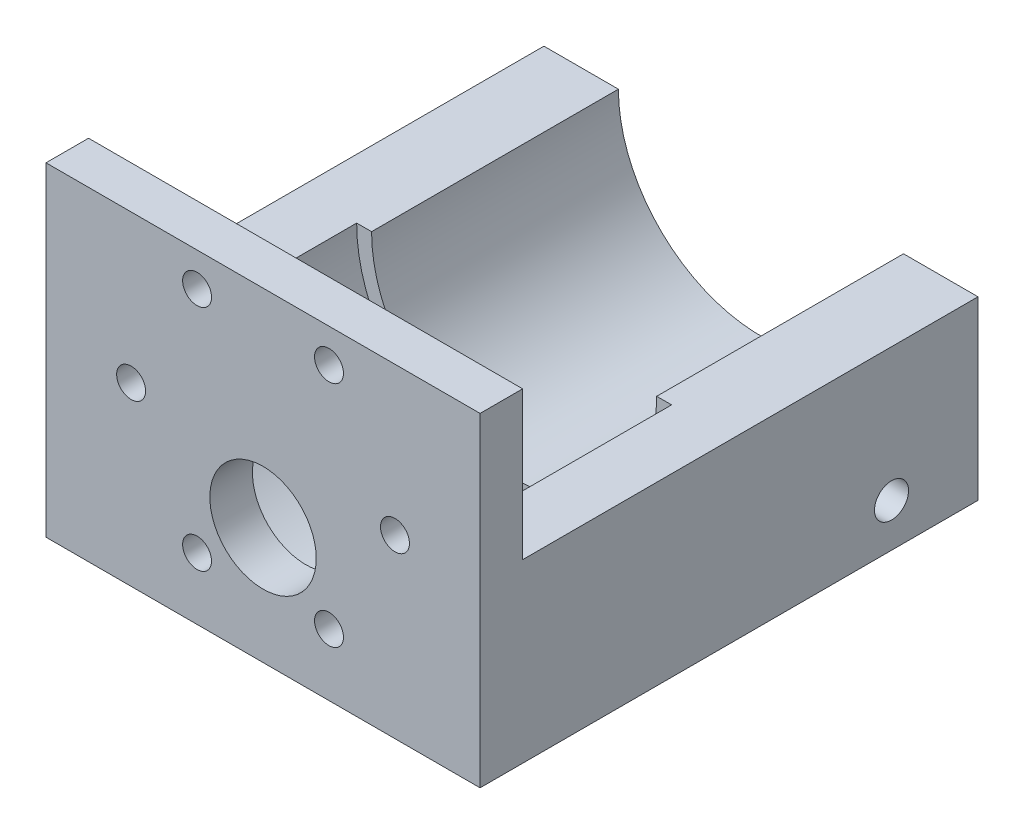
SolidWorks part; units mm, degrees
ref_plane "Front Plane" through (0, 0, 0) normal (0, 0, 1) x (1, 0, 0)
ref_plane "Top Plane" through (0, 0, 0) normal (0, 1, 0) x (1, 0, 0)
ref_plane "Right Plane" through (0, 0, 0) normal (1, 0, 0) x (0, 0, -1)
sketch "Sketch1" plane through (0, 0, 0) normal (0, 0, 1) x (1, 0, 0)
  line L0 (18.5, 0) -> (25.5, 0)
  line L1 (25.5, 0) -> (25.5, -20.716)
  line L2 (25.5, -20.716) -> (-25.5, -20.716)
  line L3 (-25.5, -20.716) -> (-25.5, 0)
  line L4 (-25.5, 0) -> (-18.5, 0)
  arc A0 (-18.5, 0) -> (18.5, 0) centre (0, 0) ccw
  dimension "D1" = 37
  dimension "D2" = 7
  dimension "D3" = 7
  dimension "D4" = 20.716
extrude "Boss-Extrude1" add sketch "Sketch1" along normal blind 24.5
sketch "Sketch2" plane through (0, 0, 24.5) normal (0, 0, 1) x (1, 0, 0)
  line L0 (-25.5, -20.716) -> (25.5, -20.716)
  line L2 (-25.5, -20.716) -> (-25.5, 17.384)
  line L5 (25.5, -20.716) -> (25.5, 17.384)
  line L6 (25.5, 17.384) -> (-25.5, 17.384)
  circle A0 centre (0, -7) radius 6.25
  circle A1 centre (15.5, 0) radius 1.7
  circle A2 centre (-7.75, -13.4234) radius 1.7
  circle A3 centre (-7.75, 13.4234) radius 1.7
  circle A4 centre (-15.5, 0) radius 1.7
  circle A5 centre (7.75, 13.4234) radius 1.7
  circle A6 centre (7.75, -13.4234) radius 1.7
  point P17 (0, 0)
  point P24 (0, 0)
  dimension "D4" = 12.5
  dimension "D6" = 3.4
  dimension "D9" = 3.4
  dimension "D3" = 7
  dimension "D5" = 15.5
  dimension "D8" = 15.5
  dimension "D7" = 3
  dimension "D10" = 3
extrude "Boss-Extrude2" add sketch "Sketch2" along normal blind 5
sketch "Sketch3" plane through (0, 0, 0) normal (0, 0, -1) x (-1, 0, 0)
  line L0 (16.75, 0) -> (25.5, 0)
  line L1 (25.5, 0) -> (25.5, -20.716)
  line L2 (25.5, -20.716) -> (-25.5, -20.716)
  line L3 (-25.5, -20.716) -> (-25.5, 0)
  line L4 (-25.5, 0) -> (-16.75, 0)
  arc A0 (-16.75, 0) -> (16.75, 0) centre (0, 0) ccw
  dimension "D1" = 33.5
  dimension "D2" = 8.75
extrude "Boss-Extrude3" add sketch "Sketch3" along normal blind 29
sketch "Sketch4" plane through (0, -20.716, 0) normal (0, -1, 0) x (1, 0, 0)
  line L0 (-25.5, 29.5) -> (25.5, 29.5) construction
  line L1 (-25.5, 29.5) -> (-25.5, -29) construction
  line L2 (25.5, 29.5) -> (25.5, -29) construction
  line L3 (25.5, -29) -> (-25.5, -29) construction
  circle A0 centre (-21.69, 25.69) radius 2
  circle A1 centre (21.69, 25.69) radius 2
  circle A2 centre (-21.69, -25.19) radius 2
  circle A3 centre (21.69, -25.19) radius 2
  point P8 (22.0131, 20.9123)
  dimension "D1" = 4
  dimension "D2" = 4
  dimension "D3" = 4
  dimension "D4" = 4
  dimension "D5" = 3.81
  dimension "D6" = 3.81
  dimension "D7" = 3.81
  dimension "D9" = 3.81
  dimension "D10" = 3.81
  dimension "D11" = 3.81
  dimension "D12" = 3.81
  dimension "D13" = 43.38
  dimension "D14" = 50.88
  dimension "D8" = 3.81
extrude "Cut-Extrude1" cut sketch "Sketch4" against normal blind 7
sketch "Sketch5" plane through (-25.5, 0, 0) normal (-1, 0, 0) x (0, 0, 1)
  line L0 (29.5, -20.716) -> (-29, -20.716) construction
  line L1 (-29, -20.716) -> (-29, 0) construction
  circle A0 centre (-18.84, -15.636) radius 2
  point P6 (-23.4252, -17.905)
  dimension "D1" = 4
  dimension "D3" = 10.16
  dimension "D2" = 5.08
sketch "Sketch6" plane through (25.5, 0, 0) normal (1, 0, 0) x (0, 0, -1)
  line L1 (-24.5, 0) -> (29, 0) construction
  circle A0 centre (18.84, -15.636) radius 2
  dimension "D1" = 4
  dimension "D2" = 15.636
extrude "Cut-Extrude2" cut sketch "Sketch5" against normal blind 7
extrude "Cut-Extrude3" cut sketch "Sketch6" against normal blind 7
